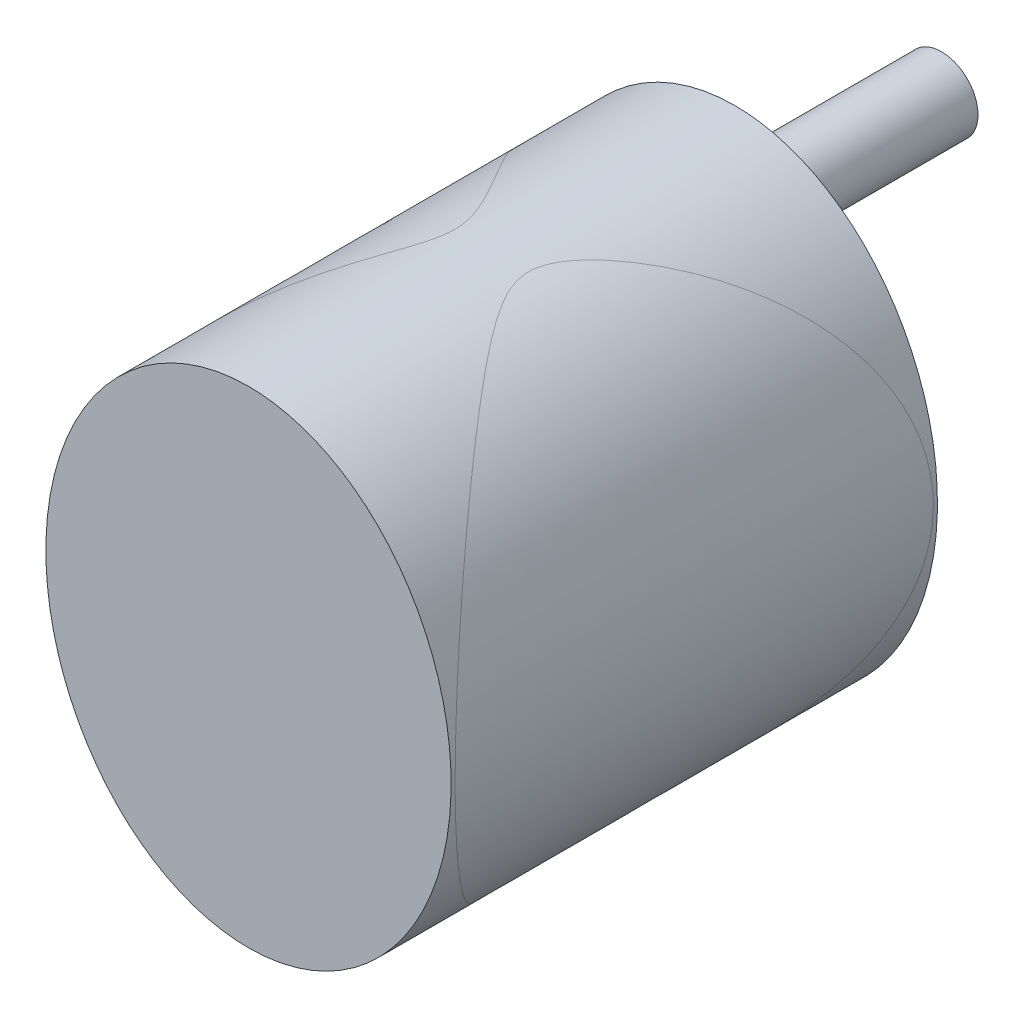
SolidWorks part; units mm, degrees
material "ABS"
ref_plane "Plan de face" through (0, 0, 0) normal (0, 0, 1) x (1, 0, 0)
ref_plane "Plan de dessus" through (0, 0, 0) normal (0, 1, 0) x (1, 0, 0)
ref_plane "Plan de droite" through (0, 0, 0) normal (1, 0, 0) x (0, 0, -1)
sketch "Esquisse1" plane through (0, 0, 0) normal (0, 0, 1) x (1, 0, 0)
  ellipse E0 centre (0, 0) end of major axis (0, 3) minor radius 2.5
extrude "Extrusion1" add sketch "Esquisse1" along normal blind 6
sketch "Esquisse2" plane through (0, 0, 0) normal (1, 0, 0) x (0, 0, -1)
  circle A0 centre (-3, 0) radius 2.95
split "Fractionner3" trim tools "Esquisse2" resulting bodies 106 107
ref_plane "Plan1" through (0, 0, -2) normal (0, 0, 1) x (1, 0, 0)
sketch "Esquisse3" plane through (0, 0, -2) normal (0, 0, 1) x (1, 0, 0)
  circle A0 centre (0.55, 2.4) radius 0.45
  circle A1 centre (-0.55, -2.4) radius 0.45
  dimension "D1" = 2.4
  dimension "D3" = 2.4
  dimension "D2" = 0.55
  dimension "D4" = 0.55
extrude "Extrusion3" add sketch "Esquisse3" along normal up to surface (3.2846 mm away)
